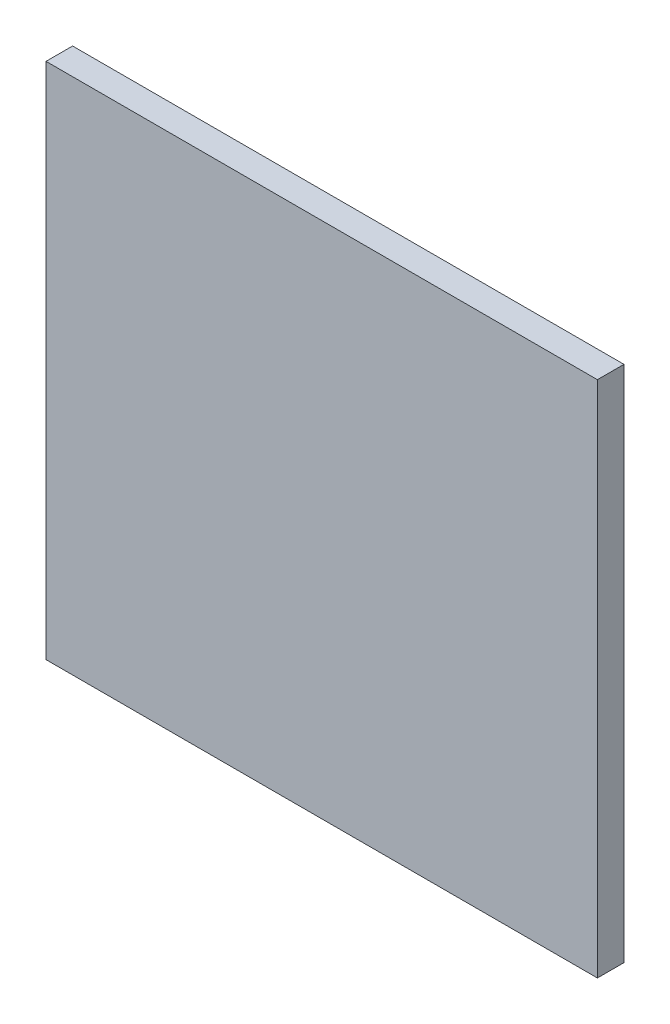
SolidWorks part; units mm, degrees
ref_plane "Front Plane" through (0, 0, 0) normal (0, 0, 1) x (1, 0, 0)
ref_plane "Top Plane" through (0, 0, 0) normal (0, 1, 0) x (1, 0, 0)
ref_plane "Right Plane" through (0, 0, 0) normal (1, 0, 0) x (0, 0, -1)
sketch "Sketch1" plane through (0, 0, 0) normal (0, 0, 1) x (1, 0, 0)
  line L1 (0, 0) -> (41.5, 0)
  line L2 (0, 0) -> (0, 39)
  line L3 (0, 39) -> (41.5, 39)
  line L4 (41.5, 0) -> (41.5, 39)
  dimension "D1" = 41.5
  dimension "35" = 39
extrude "Boss-Extrude1" add sketch "Sketch1" along normal blind 2
